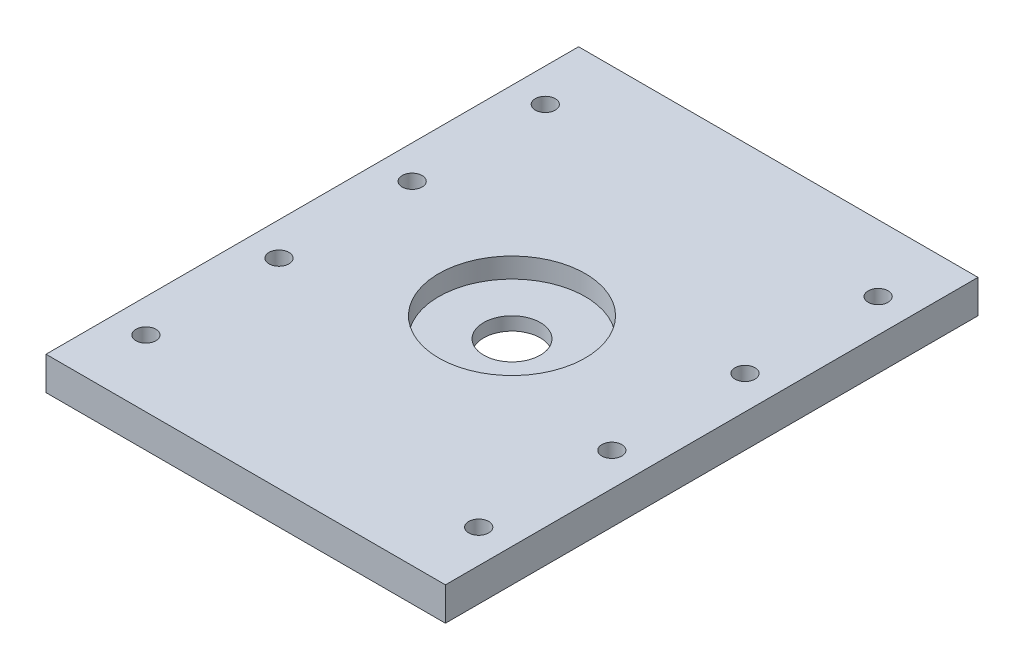
SolidWorks part; units mm, degrees
ref_plane "Front Plane" through (0, 0, 0) normal (0, 0, 1) x (1, 0, 0)
ref_plane "Top Plane" through (0, 0, 0) normal (0, 1, 0) x (1, 0, 0)
ref_plane "Right Plane" through (0, 0, 0) normal (1, 0, 0) x (0, 0, -1)
sketch "Sketch1" plane through (0, 0, 0) normal (0, 1, 0) x (1, 0, 0)
  line L1 (-30, 40) -> (30, 40)
  line L2 (-30, 40) -> (-30, -40)
  line L3 (-30, -40) -> (30, -40)
  line L4 (30, 40) -> (30, -40)
  line L5 (-30, 40) -> (30, -40) construction
  line L6 (-30, -40) -> (30, 40) construction
  circle A0 centre (-25, 30) radius 1.5
  circle A1 centre (25, 30) radius 1.5
  circle A2 centre (25, 10) radius 1.5
  circle A3 centre (25, -10) radius 1.5
  circle A4 centre (25, -30) radius 1.5
  circle A5 centre (-25, 10) radius 1.5
  circle A6 centre (-25, -10) radius 1.5
  circle A7 centre (-25, -30) radius 1.5
  circle A8 centre (0, 0) radius 4.25
  point P0 (0, 0)
  dimension "D3" = 3
  dimension "D5" = 5
  dimension "D11" = 8.5
  dimension "D1" = 80
  dimension "D2" = 60
  dimension "D4" = 50
  dimension "D6" = 10
  dimension "D8" = 20
  dimension "D10" = 20
  dimension "D7" = 4
  dimension "D9" = 4
extrude "Boss-Extrude1" add sketch "Sketch1" along normal blind 5
sketch "Sketch2" plane through (0, 5, 0) normal (0, 1, 0) x (1, 0, 0)
  circle A0 centre (0, 0) radius 11
  dimension "D1" = 22
extrude "Cut-Extrude1" cut sketch "Sketch2" against normal blind 3
